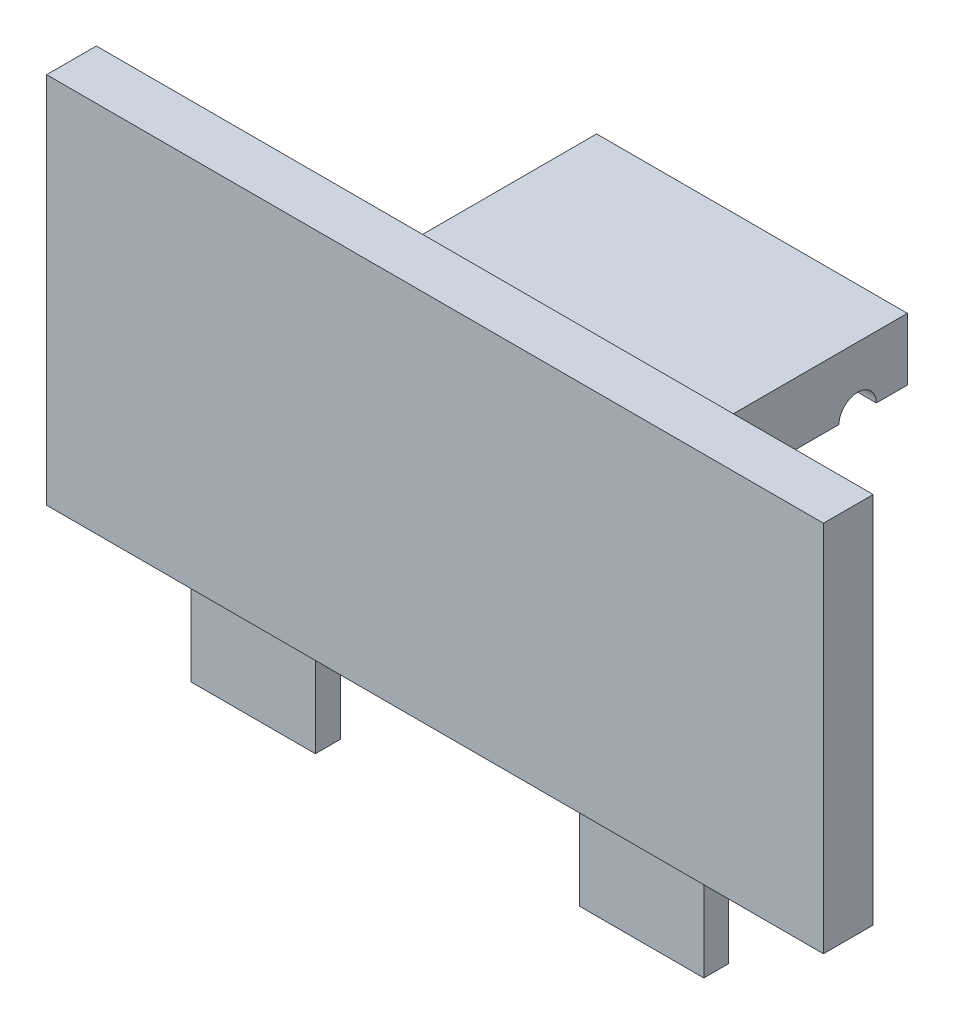
SolidWorks part; units mm, degrees
ref_plane "前视基准面" through (0, 0, 0) normal (0, 0, 1) x (1, 0, 0)
ref_plane "上视基准面" through (0, 0, 0) normal (0, 1, 0) x (1, 0, 0)
ref_plane "右视基准面" through (0, 0, 0) normal (1, 0, 0) x (0, 0, -1)
sketch "草图1" plane through (0, 0, 0) normal (0, 1, 0) x (1, 0, 0)
  line L1 (0, 0) -> (125, 0)
  line L2 (0, 0) -> (0, 8)
  line L3 (0, 8) -> (125, 8)
  line L4 (125, 0) -> (125, 8)
  dimension "D1" = 8
  dimension "D2" = 125
extrude "凸台-拉伸1" add sketch "草图1" along normal blind 60
sketch "草图2" plane through (0, 0, -8) normal (0, 0, -1) x (-1, 0, 0)
  line L0 (-125, 0) -> (0, 0) construction
  line L5 (-87.5, 45) -> (-37.5, 45)
  line L6 (-87.5, 45) -> (-87.5, 35)
  line L7 (-87.5, 35) -> (-37.5, 35)
  line L8 (-37.5, 45) -> (-37.5, 35)
  line L9 (-87.5, 45) -> (-37.5, 35) construction
  line L10 (-87.5, 35) -> (-37.5, 45) construction
  line L11 (-125, 60) -> (-125, 0) construction
  point P0 (-62.5, 40)
  dimension "D1" = 40
  dimension "D2" = 62.5
  dimension "D3" = 10
  dimension "D4" = 50
extrude "凸台-拉伸2" add sketch "草图2" along normal blind 43
sketch "草图3" plane through (0, 0, 0) normal (0, -1, 0) x (1, 0, 0)
  line L0 (62.5, -8) -> (62.5, 0) construction
  line L1 (87.5, -8) -> (37.5, -8) construction
  line L2 (0, 0) -> (125, 0) construction
  line L3 (62.5, 0) -> (0, -8) construction
  line L4 (0, -8) -> (0, 0) construction
  line L5 (125, -8) -> (0, -8) construction
  line L6 (0, 0) -> (62.5, -8) construction
  line L7 (62.5, -8) -> (125, 0) construction
  line L9 (21.25, -2) -> (41.25, -2)
  line L10 (62.5, 0) -> (125, -8) construction
  line L11 (21.25, -2) -> (21.25, -6)
  line L12 (21.25, -6) -> (41.25, -6)
  line L13 (41.25, -2) -> (41.25, -6)
  line L14 (21.25, -2) -> (41.25, -6) construction
  line L15 (21.25, -6) -> (41.25, -2) construction
  line L16 (83.75, -2) -> (103.75, -2)
  line L17 (83.75, -2) -> (83.75, -6)
  line L18 (83.75, -6) -> (103.75, -6)
  line L19 (103.75, -2) -> (103.75, -6)
  line L20 (83.75, -2) -> (103.75, -6) construction
  line L21 (83.75, -6) -> (103.75, -2) construction
  point P12 (93.75, -4)
  point P16 (31.25, -4)
extrude "凸台-拉伸3" add sketch "草图3" along normal blind 15
sketch "草图4" plane through (0, 35, 0) normal (0, -1, 0) x (1, 0, 0)
  line L0 (37.5, -51) -> (37.5, -8) construction
  line L1 (37.5, -46) -> (87.5, -46)
  line L2 (37.5, -46) -> (37.5, -43)
  line L3 (37.5, -43) -> (87.5, -43)
  line L4 (87.5, -46) -> (87.5, -43)
  line L5 (87.5, -51) -> (87.5, -8) construction
  line L6 (87.5, -8) -> (37.5, -8) construction
  dimension "D1" = 3
  dimension "D2" = 35
revolve "切除-旋转1" cut sketch "草图4" angle 360 about L3
